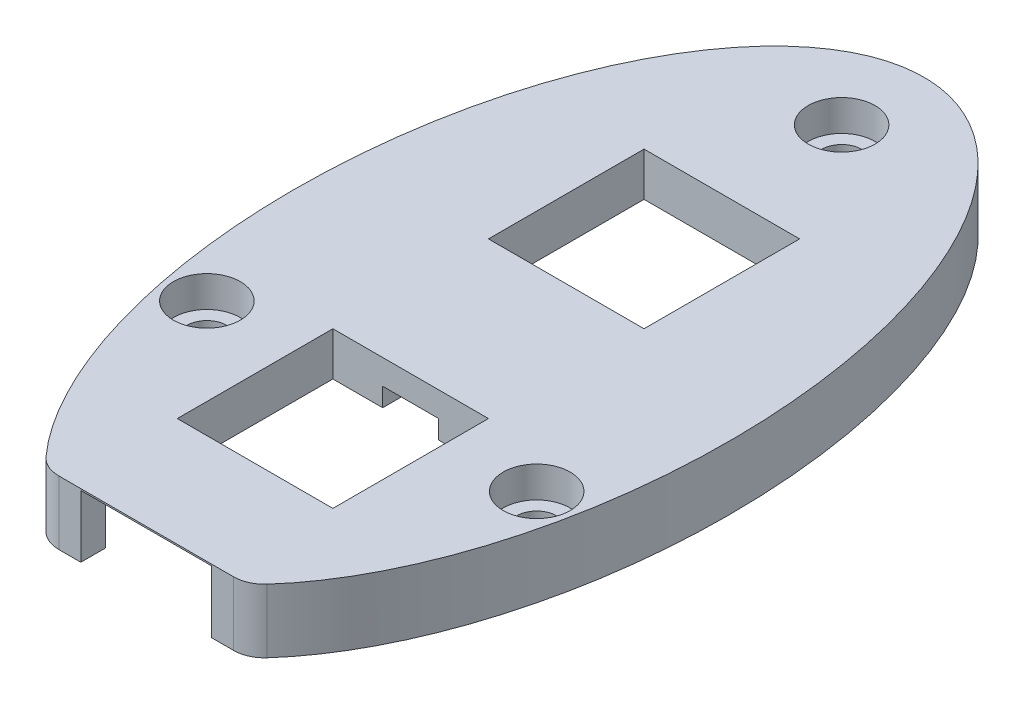
SolidWorks part; units mm, degrees
ref_plane "Front Plane" through (0, 0, 0) normal (0, 0, 1) x (1, 0, 0)
ref_plane "Top Plane" through (0, 0, 0) normal (0, 1, 0) x (1, 0, 0)
ref_plane "Right Plane" through (0, 0, 0) normal (1, 0, 0) x (0, 0, -1)
sketch "Sketch1" plane through (0, 0, 0) normal (0, 1, 0) x (1, 0, 0)
  line L0 (-8.2173, -29.845) -> (8.2173, -29.845)
  ellipse E0 centre (0, 0) end of major axis (0, -33.655) minor radius 17.78 (8.2173, -29.845) -> (-8.2173, -29.845) ccw
  dimension "D1" = 67.31
  dimension "D2" = 35.56
  dimension "D3" = 63.5
extrude "Boss-Extrude1" add sketch "Sketch1" against normal blind 2.032
sketch "Sketch17" plane through (0, 0, 0) normal (0, 1, 0) x (1, 0, 0)
  line L0 (0, 0) -> (0, 50.5429) construction
  line L1 (-6.35, 17.145) -> (6.35, 17.145)
  line L2 (-6.35, 17.145) -> (-6.35, 4.445)
  line L3 (-6.35, 4.445) -> (6.35, 4.445)
  line L4 (6.35, 17.145) -> (6.35, 4.445)
  line L5 (-6.35, 17.145) -> (6.35, 4.445) construction
  line L6 (-6.35, 4.445) -> (6.35, 17.145) construction
  line L7 (-6.35, -8.255) -> (6.35, -8.255)
  line L8 (-6.35, -8.255) -> (-6.35, -20.955)
  line L9 (-6.35, -20.955) -> (6.35, -20.955)
  line L10 (6.35, -8.255) -> (6.35, -20.955)
  line L11 (-6.35, -8.255) -> (6.35, -20.955) construction
  line L12 (-6.35, -20.955) -> (6.35, -8.255) construction
  line L13 (-8.2173, -29.845) -> (8.2173, -29.845) construction
  point P0 (0, 10.795)
  point P5 (0, -14.605)
  dimension "D1" = 12.7
  dimension "D2" = 15.24
  dimension "D3" = 40.64
extrude "Cut-Extrude13" cut sketch "Sketch17" against normal through all
sketch "Sketch18" plane through (0, -2.032, 0) normal (0, 1, 0) x (1, 0, 0)
  line L105 (-8.382, 19.177) -> (-8.382, 2.413)
  line L106 (-8.382, 2.413) -> (8.382, 2.413)
  line L107 (8.382, 2.413) -> (8.382, 19.177)
  line L108 (8.382, 19.177) -> (-8.382, 19.177)
  line L109 (-8.382, 19.177) -> (-8.382, 2.413)
  line L110 (-8.382, 2.413) -> (-2.286, 2.413)
  line L111 (8.382, 2.413) -> (8.382, 19.177)
  line L112 (8.382, 19.177) -> (-8.382, 19.177)
  line L113 (-6.35, 17.145) -> (-6.35, 4.445) construction
  line L114 (6.35, 17.145) -> (-6.35, 17.145) construction
  line L115 (-6.35, 4.445) -> (6.35, 4.445) construction
  line L116 (6.35, 4.445) -> (6.35, 17.145) construction
  line L117 (8.382, -22.987) -> (8.382, -6.223)
  line L118 (8.382, -6.223) -> (-8.382, -6.223)
  line L119 (-8.382, -6.223) -> (-8.382, -22.987)
  line L120 (-8.382, -22.987) -> (8.382, -22.987)
  line L121 (8.382, -22.987) -> (8.382, -6.223)
  line L122 (8.382, -6.223) -> (2.286, -6.223)
  line L123 (-8.382, -6.223) -> (-8.382, -22.987)
  line L124 (-8.382, -22.987) -> (8.382, -22.987)
  line L125 (-6.35, 17.145) -> (-6.35, 4.445)
  line L126 (6.35, 17.145) -> (-6.35, 17.145)
  line L127 (-6.35, 4.445) -> (-2.286, 4.445)
  line L128 (6.35, 4.445) -> (6.35, 17.145)
  line L129 (6.35, -8.255) -> (-6.35, -8.255) construction
  line L130 (6.35, -20.955) -> (6.35, -8.255) construction
  line L131 (-6.35, -20.955) -> (6.35, -20.955) construction
  line L132 (-6.35, -8.255) -> (-6.35, -20.955) construction
  line L133 (6.35, -8.255) -> (2.286, -8.255)
  line L134 (6.35, -20.955) -> (6.35, -8.255)
  line L135 (-6.35, -20.955) -> (6.35, -20.955)
  line L136 (-6.35, -8.255) -> (-6.35, -20.955)
  line L137 (-2.286, -8.255) -> (-2.286, -6.223)
  line L139 (2.286, 4.445) -> (2.286, 2.413)
  line L141 (0, 0) -> (0, 31.2149) construction
  line L142 (2.286, 2.413) -> (8.382, 2.413)
  line L143 (2.286, 4.445) -> (6.35, 4.445)
  line L144 (-2.286, -6.223) -> (-8.382, -6.223)
  line L145 (-2.286, -8.255) -> (-6.35, -8.255)
  line L146 (-2.286, 2.413) -> (-2.286, 4.445)
  line L147 (2.286, -6.223) -> (2.286, -8.255)
  dimension "D3" = 4.572
  dimension "D1" = 2.032
  dimension "D2" = 2.032
extrude "LightBox" add sketch "Sketch18" against normal blind 1.524
sketch "Sketch19" plane through (0, -2.032, 0) normal (0, -1, 0) x (1, 0, 0)
  line L0 (0, 0) -> (0, 18.966) construction
  circle A0 centre (-13.462, 11.43) radius 1.6256
  circle A1 centre (13.462, 11.43) radius 1.6256
  circle A2 centre (13.462, 11.43) radius 2.921
  circle A3 centre (-13.462, 11.43) radius 2.921
  circle A4 centre (0, -26.924) radius 1.6256
  circle A5 centre (0, -26.924) radius 2.921
  dimension "D3" = 3.2512
  dimension "D4" = 5.842
  dimension "D1" = 11.43
  dimension "D2" = 26.924
  dimension "D5" = 26.924
extrude "Boss-Screws" add sketch "Sketch19" along normal up to surface (1.524 mm away) up to face at (0, -3.556, 12.1497)
sketch "Sketch20" plane through (0, -2.032, 0) normal (0, -1, 0) x (1, 0, 0)
  line L0 (-8.2173, 29.845) -> (8.2173, 29.845) construction
  line L1 (-8.2173, 29.845) -> (8.2173, 29.845)
  line L2 (-7.3554, 27.813) -> (7.3554, 27.813)
  ellipse E0 centre (0, 0) end of major axis (0, 33.655) minor radius 17.78 (-8.2173, 29.845) -> (8.2173, 29.845) ccw construction
  ellipse E1 centre (0, 0) end of major axis (0, 33.655) minor radius 17.78 (-8.2173, 29.845) -> (8.2173, 29.845) ccw
  spline S0 degree 1 poles (-7.3554, 27.813) (7.3554, 27.813) knots 0 0 1 1 construction
  spline S1 degree 3 poles (-7.3554, 27.813) (-7.747, 27.3876) (-8.4711, 26.523) (-9.5515, 24.9917) (-10.5644, 23.2899) (-11.8281, 20.7908) (-13.2119, 17.2782) (-14.4988, 12.5627) (-15.3664, 7.4855) (-15.9268, 0.4294) (-15.4665, -8.5478) (-13.1226, -18.3463) (-9.3021, -26.0406) (-5.4001, -29.9288) (-2.2834, -31.3895) (0, -31.7398) (2.2834, -31.3895) (5.4001, -29.9288) (9.3021, -26.0406) (13.1226, -18.3463) (15.4665, -8.5478) (15.9268, 0.4294) (15.3664, 7.4855) (14.4988, 12.5627) (13.2119, 17.2782) (11.8281, 20.7908) (10.5644, 23.2899) (9.5515, 24.9917) (8.4711, 26.523) (7.747, 27.3876) (7.3554, 27.813) knots 0.521032 0.521032 0.521032 0.521032 0.602925 0.684817 0.76671 0.848602 1.012387 1.176172 1.339957 1.503742 1.831312 2.158882 2.486453 2.814023 2.977808 3.141593 3.305378 3.469163 3.796733 4.124303 4.451873 4.779443 4.943228 5.107013 5.270798 5.434583 5.516476 5.598368 5.680261 5.762153 5.762153 5.762153 5.762153
  dimension "D1" = 2.032
extrude "FlangeOuter" add sketch "Sketch20" along normal blind 3.175
sketch "Sketch27" plane through (0, -3.556, 0) normal (0, -1, 0) x (1, 0, 0)
  circle A0 centre (-13.462, 11.43) radius 1.6256
  arc A1 (-14.3669, 12.7804) -> (-14.8219, 10.5393) centre (-13.462, 11.43) ccw construction
  circle A2 centre (13.462, 11.43) radius 1.6256
  arc A3 (14.3669, 12.7804) -> (14.8219, 10.5393) centre (13.462, 11.43) ccw construction
  circle A4 centre (0, -26.924) radius 1.6256 construction
  circle A5 centre (0, -26.924) radius 1.6256
extrude "Cut-Extrude16" cut sketch "Sketch27" against normal through all and the other way through all
sketch "Sketch28" plane through (0, 0, 0) normal (0, 1, 0) x (1, 0, 0)
  circle A0 centre (-13.462, -11.43) radius 2.7305
  circle A1 centre (13.462, -11.43) radius 2.7305
  circle A2 centre (0, 26.924) radius 2.7305
  dimension "D1" = 5.461
extrude "Cut-Extrude17" cut sketch "Sketch28" against normal blind 2.54
sketch "Sketch21" plane through (0, 0, 29.845) normal (0, 0, 1) x (1, 0, 0)
  line L0 (8.2173, -5.207) -> (-8.2173, -5.207) construction
  line L1 (-5.334, -5.207) -> (5.334, -5.207)
  line L2 (-5.334, -5.207) -> (-5.334, -0.127)
  line L3 (-5.334, -0.127) -> (5.334, -0.127)
  line L4 (5.334, -5.207) -> (5.334, -0.127)
  line L5 (0, 0) -> (0, -14.4473) construction
  line L6 (-8.2173, 0) -> (8.2173, 0) construction
  dimension "D1" = 5.08
  dimension "D2" = 10.668
extrude "Cut-Extrude14" cut sketch "Sketch21" against normal up to next
sketch "Sketch22" plane through (0, 0, 0) normal (0, 1, 0) x (1, 0, 0)
  line L0 (0, 0) -> (0, 47.2593) construction
  line L1 (-25.4, 53.34) -> (25.4, 53.34)
  line L2 (-25.4, 53.34) -> (-25.4, 27.94)
  line L3 (-25.4, 27.94) -> (25.4, 27.94)
  line L4 (25.4, 53.34) -> (25.4, 27.94)
  dimension "D1" = 27.94
  dimension "D2" = 25.4
  dimension "D3" = 50.8
extrude "Cut-Extrude15" [suppressed] cut sketch "Sketch22" against normal offset from surface (1.524 mm away) 2.032
sketch "Sketch25" [suppressed] plane through (0, -1.524, 0) normal (0, 1, 0) x (1, 0, 0)
  line L0 (-9.2845, 28.702) -> (9.2845, 28.702)
  line L1 (-9.912, 27.94) -> (-2.5344, 27.94) construction
  ellipse E0 centre (0, 0) end of major axis (0, -33.655) minor radius 17.78 (9.912, 27.94) -> (-9.912, 27.94) ccw construction
  ellipse E1 centre (0, 0) end of major axis (0, -33.655) minor radius 17.78 (9.2845, 28.702) -> (-9.2845, 28.702) ccw
  dimension "D1" = 0.762
extrude "Boss-Extrude8" [suppressed] add sketch "Sketch25" against normal through all
fillet "Fillet1" radius 2.54 2 edges at (8.2173, -2.6035, 29.845) (-8.2173, -2.6035, 29.845)
